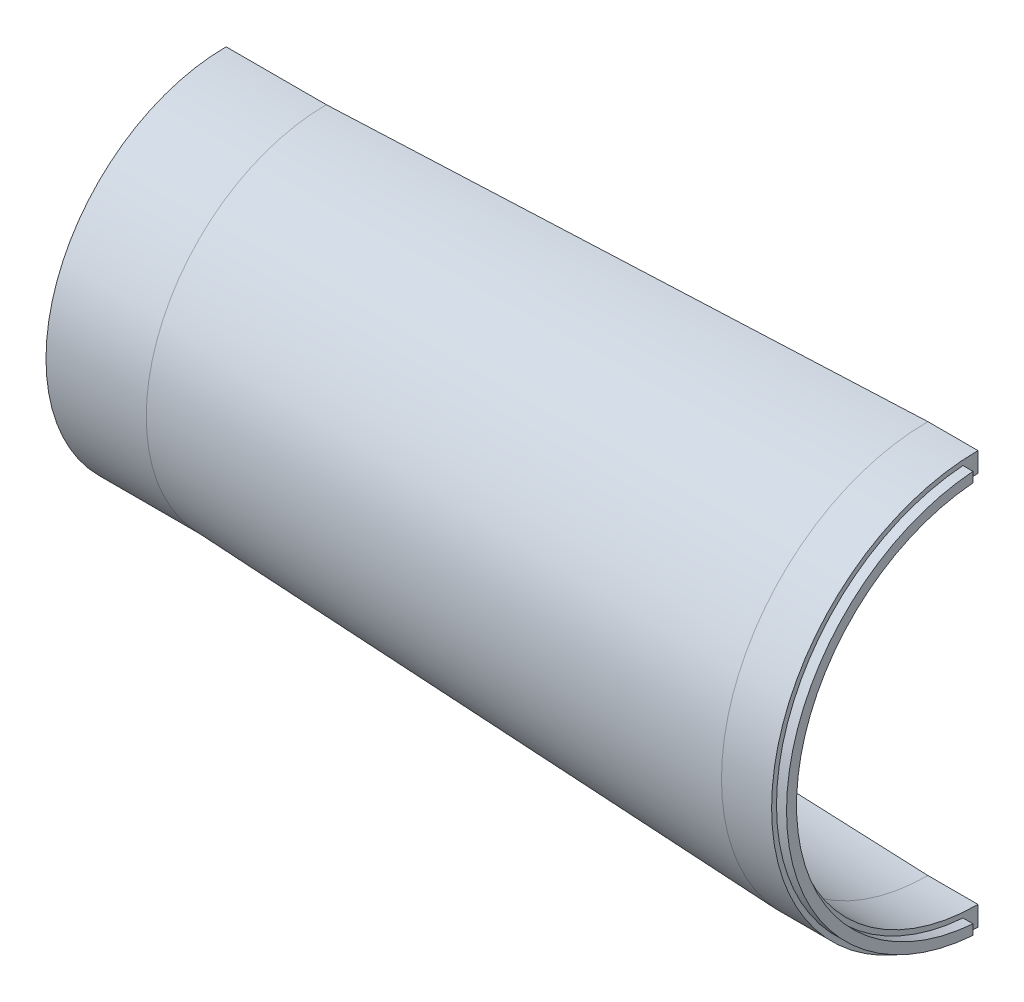
SolidWorks part; units mm, degrees
ref_plane "Front Plane" through (0, 0, 0) normal (0, 0, 1) x (1, 0, 0)
ref_plane "Top Plane" through (0, 0, 0) normal (0, 1, 0) x (1, 0, 0)
ref_plane "Right Plane" through (0, 0, 0) normal (1, 0, 0) x (0, 0, -1)
sketch "Sketch2" plane through (0, 0, 0) normal (0, 0, 1) x (1, 0, 0)
  line L0 (0, 0) -> (0, 40.64)
  line L1 (0, 0) -> (4.9987, 0)
  line L2 (4.9987, 0) -> (4.9987, 40.64)
  line L3 (0, 40.64) -> (0, 45.6387)
  line L4 (0, 45.6387) -> (25.4, 45.6387)
  line L6 (4.9987, 40.64) -> (25.4, 40.64)
  line L8 (190.5, 52.2926) -> (177.8, 52.2926)
  line L9 (177.8, 52.2926) -> (25.4, 45.6387)
  line L10 (190.5, 47.2939) -> (177.8, 47.2939)
  line L11 (177.8, 47.2939) -> (25.4, 40.64)
  line L12 (190.5, 52.2926) -> (190.5, 47.2939)
  dimension "D8" = 4.9987
  dimension "D1" = 40.64
  dimension "D2" = 4.9987
  dimension "D3" = 40.64
  dimension "D4" = 4.9987
  dimension "D5" = 25.4
  dimension "D6" = 152.4
  dimension "D7" = 12.7
  dimension "D9" = 182.5
  dimension "D10" = 12.7
revolve "Revolve2" add sketch "Sketch2" angle 180 about L1
sketch "Sketch4" plane through (0, 0, 0) normal (-1, 0, 0) x (0, 0, 1)
  line L0 (0, -45.6387) -> (0, 45.6387) construction
  line L1 (0, 0) -> (20.32, 0)
  line L2 (0, -20.32) -> (0, 20.32)
  line L3 (0, 20.32) -> (20.32, 20.32)
  line L4 (20.32, -20.32) -> (20.32, 20.32)
  line L5 (0, -20.32) -> (20.32, -20.32)
  line M6 (0, 45.6387) -> (0, -45.6387)
  dimension "D1" = 20.32
  dimension "D2" = 20.32
extrude "Cut-Extrude2" cut sketch "Sketch4" against normal blind 32.004 contours L1 L4 L3 M6 | L5 L4 L1 M6
sketch "Sketch5" plane through (0, 0, 0) normal (0, 0, -1) x (-1, 0, 0)
  line L0 (-4.9987, 40.64) -> (0, 40.64) construction
  line L1 (-3.7694, 40.64) -> (-1.2294, 40.64)
  line L2 (-3.7694, 40.64) -> (-3.7694, 27.94)
  line L3 (-3.7694, 27.94) -> (-1.2294, 27.94)
  line L4 (-1.2294, 40.64) -> (-1.2294, 27.94)
  line L5 (0, 20.32) -> (0, 45.6387) construction
  line L6 (-4.9987, 40.64) -> (-4.9987, 45.6387) construction
  line L7 (-25.4, 45.6387) -> (0, 45.6387) construction
  line L8 (-152.4, 49.9543) -> (-152.4, 47.4143)
  line L9 (-4.9987, 44.4094) -> (-17.6987, 44.4094)
  line L10 (-4.9987, 44.4094) -> (-4.9987, 41.8694)
  line L11 (-4.9987, 41.8694) -> (-17.6987, 41.8694)
  line L12 (-17.6987, 44.4094) -> (-17.6987, 41.8694)
  line L13 (-152.4, 47.4143) -> (-50.8, 42.9783)
  line L14 (-50.8, 42.9783) -> (-50.8, 45.5183)
  line L15 (-50.8, 45.5183) -> (-152.4, 49.9543)
  line L16 (-177.8, 52.2926) -> (-25.4, 45.6387) construction
  line L17 (-50.8, 45.5183) -> (-50.8, 46.7477) construction
  line L18 (-50.8, 42.9783) -> (-50.8, 41.749) construction
  line L19 (-25.4, 40.64) -> (-177.8, 47.2939) construction
  line L20 (-152.4, 46.1849) -> (-152.4, 47.4143) construction
  line L21 (-152.4, 49.9543) -> (-152.4, 51.1837) construction
  line L22 (0, 0) -> (-190.5, 0) construction
  line L23 (-190.5, 47.2939) -> (-190.5, -47.2939) construction
  line L24 (-50.8, -42.9783) -> (-50.8, -45.5183)
  line L25 (-152.4, -47.4143) -> (-50.8, -42.9783)
  line L26 (-152.4, -49.9543) -> (-152.4, -47.4143)
  line L27 (-50.8, -45.5183) -> (-152.4, -49.9543)
  line L28 (-4.9987, -41.8694) -> (-17.6987, -41.8694)
  line L29 (-17.6987, -44.4094) -> (-17.6987, -41.8694)
  line L30 (-4.9987, -44.4094) -> (-17.6987, -44.4094)
  line L31 (-4.9987, -44.4094) -> (-4.9987, -41.8694)
  line L32 (-3.7694, -27.94) -> (-1.2294, -27.94)
  line L33 (-1.2294, -40.64) -> (-1.2294, -27.94)
  line L34 (-3.7694, -40.64) -> (-1.2294, -40.64)
  line L35 (-3.7694, -40.64) -> (-3.7694, -27.94)
  point P9 (-2.4994, 40.64)
  point P10 (-2.4994, 40.64)
  point P18 (-4.9987, 43.1394)
  point P19 (-4.9987, 43.1394)
  point P26 (-101.6, 48.9657)
  point P27 (-101.6, 47.7363)
  dimension "D1" = 12.7
  dimension "D2" = 2.54
  dimension "D3" = 12.7
  dimension "D4" = 2.54
  dimension "D5" = 2.54
  dimension "D6" = 2.54
  dimension "D7" = 101.6
sketch "Sketch6" plane through (190.5, 0, 0) normal (1, 0, 0) x (0, 0, -1)
  line L0 (-3.81, 50.9116) -> (-3.81, 48.3716)
  line L1 (0, 52.2926) -> (0, 47.2939) construction
  line L2 (0, 0) -> (-52.2926, 0) construction
  line L3 (-3.81, -50.9116) -> (-3.81, -48.3716)
  arc A0 (-3.81, 50.9116) -> (-3.81, -50.9116) centre (0, 0) ccw
  arc A1 (-3.81, 48.3716) -> (-3.81, -48.3716) centre (0, 0) ccw
  arc A2 (0, 52.2926) -> (0, -52.2926) centre (0, 0) ccw construction
  dimension "D3" = 51.054
  dimension "D1" = 2.54
  dimension "D2" = 3.81
extrude "Boss-Extrude2" add sketch "Sketch6" along normal blind 2.54 contours A0 L3 A1 L0
extrude "Cut-Extrude3" cut sketch "Sketch5" against normal blind 2.54 contours L15 L8 L13 L14 | L10 L9 L12 L11 | L2 L1 L4 L3 | L32 L33 L34 L35 | L28 L29 L30 L31 | L24 L27 L26 L25
